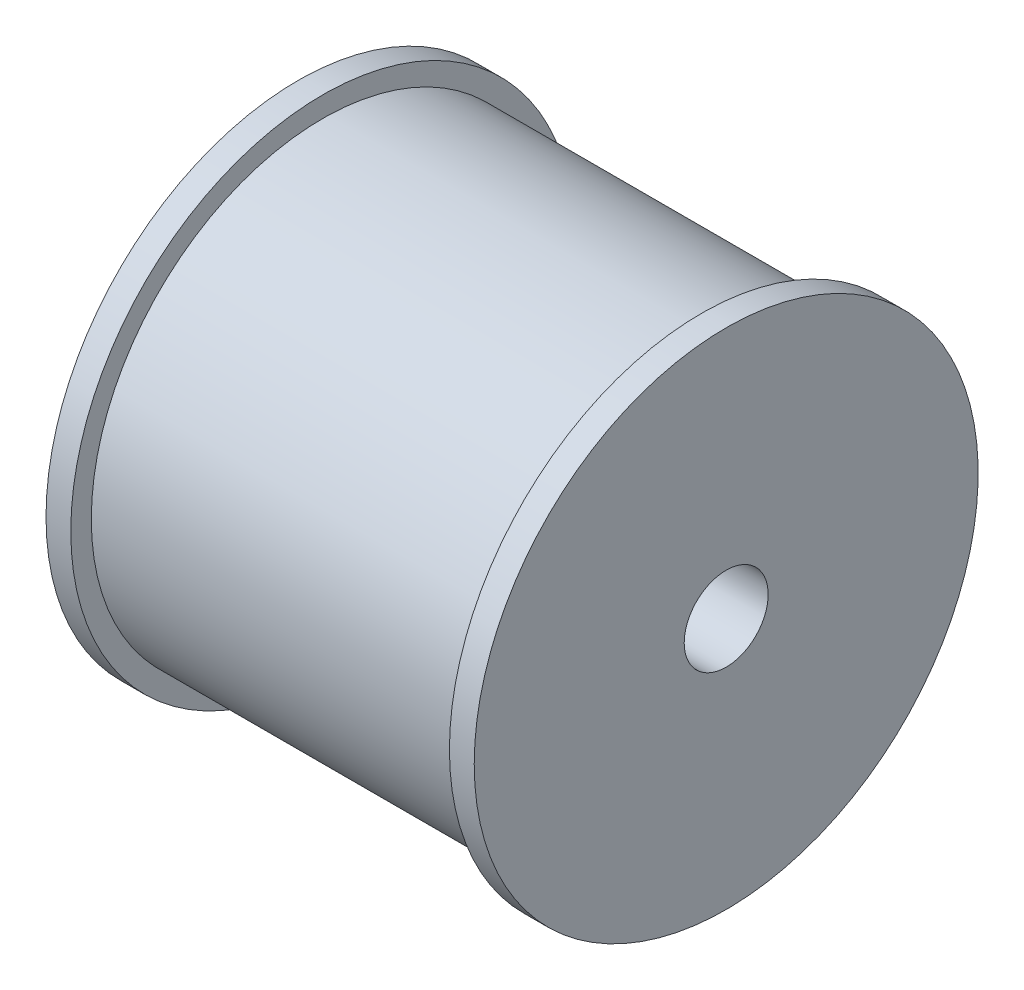
SolidWorks part; units mm, degrees
ref_plane "Front Plane" through (0, 0, 0) normal (0, 0, 1) x (1, 0, 0)
ref_plane "Top Plane" through (0, 0, 0) normal (0, 1, 0) x (1, 0, 0)
ref_plane "Right Plane" through (0, 0, 0) normal (1, 0, 0) x (0, 0, -1)
sketch "Sketch1" plane through (0, 0, 0) normal (0, 0, 1) x (1, 0, 0)
  line L0 (0, 0) -> (99.4477, 0) construction
  line L1 (0, 25.4) -> (0, 152.4)
  line L2 (0, 152.4) -> (15, 152.4)
  line L3 (15, 152.4) -> (15, 140)
  line L4 (15, 140) -> (244, 140)
  line L5 (244, 140) -> (244, 152.4)
  line L6 (244, 152.4) -> (259, 152.4)
  line L7 (259, 152.4) -> (259, 25.4)
  line L8 (259, 25.4) -> (0, 25.4)
  dimension "D1" = 25.4
  dimension "D2" = 152.4
  dimension "D3" = 259
  dimension "D4" = 15
  dimension "D5" = 15
  dimension "D6" = 140
revolve "Revolve1" add sketch "Sketch1" angle 360 about L0
sketch "Sketch2" plane through (15, 0, 0) normal (1, 0, 0) x (0, 0, -1)
  circle A0 centre (0, 0) radius 63.5
  circle A1 centre (0, 0) radius 107.95
  dimension "D1" = 127
  dimension "D2" = 215.9
surface "Surface-Extrude1" sketch "Sketch2"
